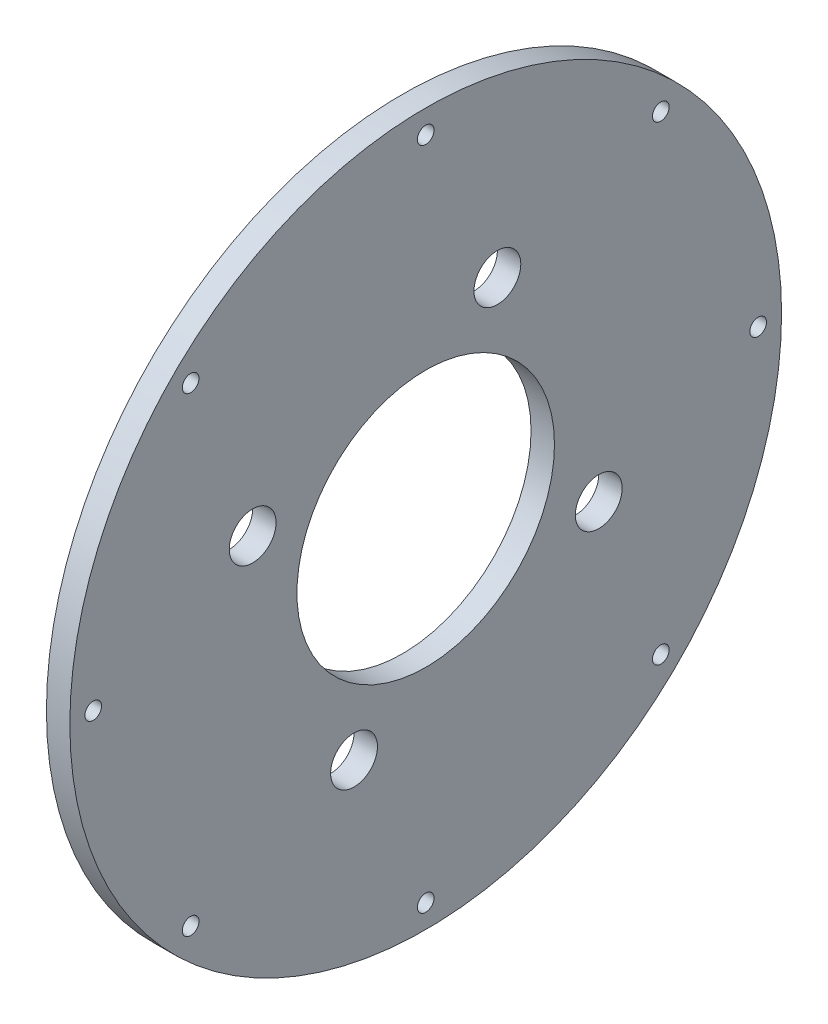
SolidWorks part; units mm, degrees
ref_plane "Front Plane" through (0, 0, 0) normal (0, 0, 1) x (1, 0, 0)
ref_plane "Top Plane" through (0, 0, 0) normal (0, 1, 0) x (1, 0, 0)
ref_plane "Right Plane" through (0, 0, 0) normal (1, 0, 0) x (0, 0, -1)
sketch "Sketch1" plane through (0, 0, 0) normal (1, 0, 0) x (0, 0, -1)
  line L0 (9.7202, 23.4665) -> (0, 0) construction
  circle A0 centre (0, 0) radius 48.26
  circle A1 centre (0, 45.085) radius 1.1303
  circle A2 centre (31.8799, 31.8799) radius 1.1303
  circle A3 centre (45.085, 0) radius 1.1303
  circle A4 centre (31.8799, -31.8799) radius 1.1303
  circle A5 centre (0, -45.085) radius 1.1303
  circle A6 centre (-31.8799, -31.8799) radius 1.1303
  circle A7 centre (-45.085, 0) radius 1.1303
  circle A8 centre (-31.8799, 31.8799) radius 1.1303
  circle A9 centre (0, 0) radius 17.4625
  circle A10 centre (9.7202, 23.4665) radius 3.175
  circle A11 centre (23.4665, -9.7202) radius 3.175
  circle A12 centre (-9.7202, -23.4665) radius 3.175
  circle A13 centre (-23.4665, 9.7202) radius 3.175
  dimension "D1" = 96.52
  dimension "D2" = 2.2606
  dimension "D4" = 34.925
  dimension "D5" = 6.35
  dimension "D3" = 45.085
  dimension "D6" = 25.4
extrude "Boss-Extrude1" add sketch "Sketch1" along normal blind 3.175
